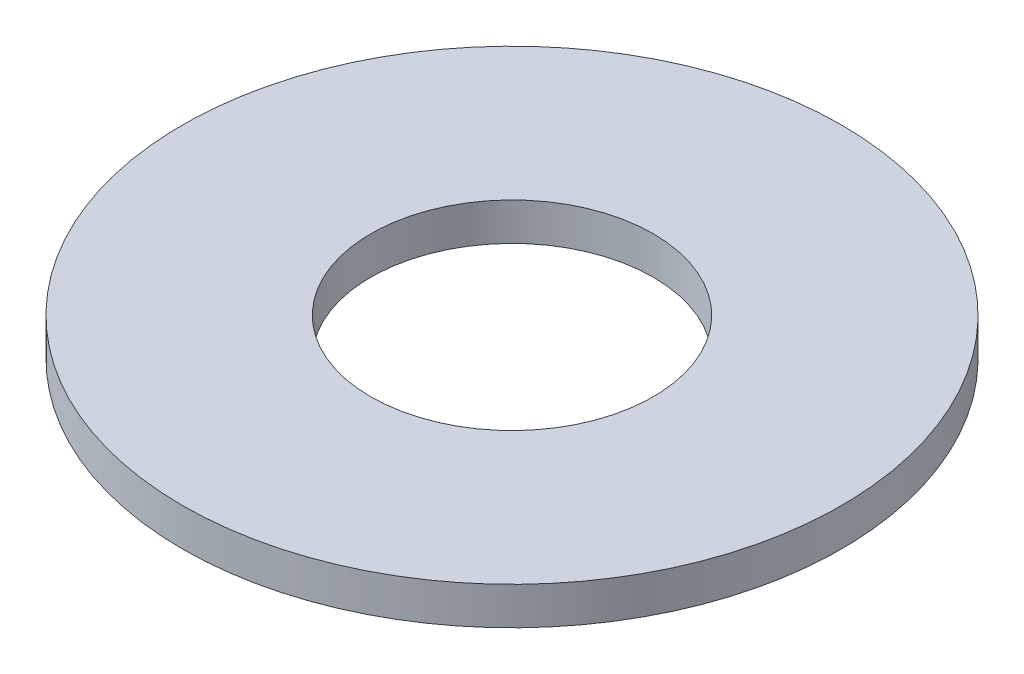
SolidWorks part; units mm, degrees
ref_plane "Front Plane" through (0, 0, 0) normal (0, 0, 1) x (1, 0, 0)
ref_plane "Top Plane" through (0, 0, 0) normal (0, 1, 0) x (1, 0, 0)
ref_plane "Right Plane" through (0, 0, 0) normal (1, 0, 0) x (0, 0, -1)
sketch "Sketch1" plane through (0, 0, 0) normal (0, 1, 0) x (1, 0, 0)
  circle A0 centre (0, 0) radius 3.5
  circle A1 centre (0, 0) radius 1.5
  dimension "D1" = 3
  dimension "D2" = 7
extrude "Boss-Extrude1" add sketch "Sketch1" along normal blind 0.4
